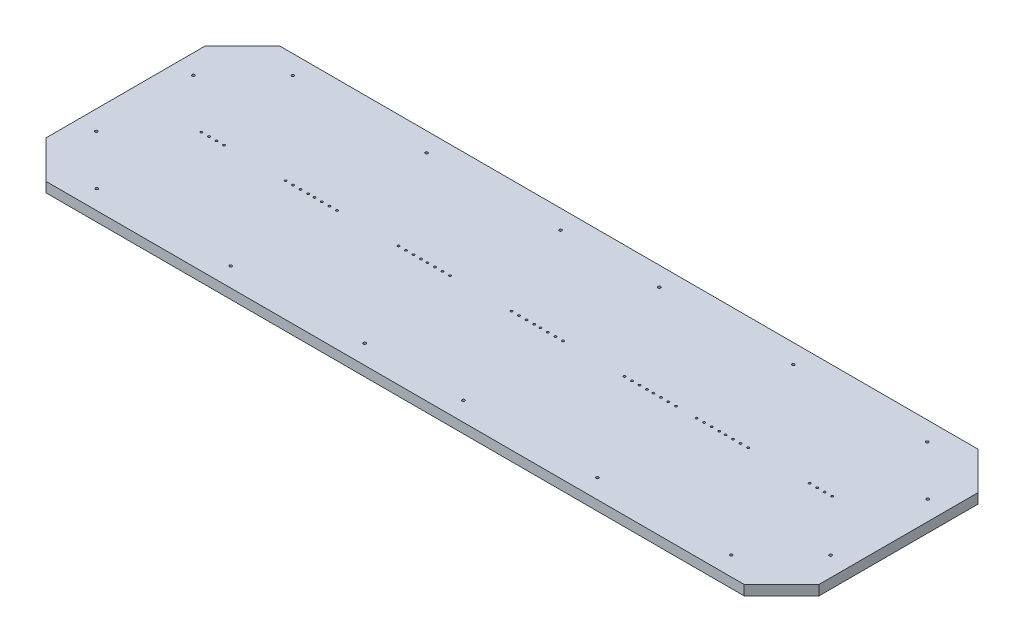
SolidWorks part; units mm, degrees
material "Pin"
ref_plane "Plan de face" through (0, 0, 0) normal (0, 0, 1) x (1, 0, 0)
ref_plane "Plan de dessus" through (0, 0, 0) normal (0, 1, 0) x (1, 0, 0)
ref_plane "Plan de droite" through (0, 0, 0) normal (1, 0, 0) x (0, 0, -1)
sketch "Esquisse1" plane through (0, 0, 0) normal (0, 1, 0) x (1, 0, 0)
  line L0 (-615.95, 126.475) -> (-615.95, -126.475)
  line L1 (-615.95, -126.475) -> (-555.95, -186.475)
  line L2 (-555.95, -186.475) -> (555.95, -186.475)
  line L3 (555.95, -186.475) -> (615.95, -126.475)
  line L4 (615.95, -126.475) -> (615.95, 126.475)
  line L5 (615.95, 126.475) -> (555.95, 186.475)
  line L6 (555.95, 186.475) -> (-555.95, 186.475)
  line L7 (-555.95, 186.475) -> (-615.95, 126.475)
  line L8 (0, 186.475) -> (0, -186.475) construction
  point P11 (0, 0)
  dimension "D1" = 135
  dimension "D3" = 1231.9
  dimension "D4" = 372.95
  dimension "D5" = 252.95
extrude "Boss.-Extru.1" add sketch "Esquisse1" along normal blind 15.875
hole_wizard "Fraisage pour vis à tête fraisée bombée #61" positions "Esquisse2" profile "Esquisse3" countersink size "#6" standard "Ansi Inch" end condition through all
sketch "Esquisse2" plane through (0, 0, 0) normal (0, -1, 0) x (-1, 0, 0)
  line L0 (0, 0) -> (0, -77.375) construction
  line L2 (0, 0) -> (138.1752, 0) construction
  point P0 (292.1, -156.075)
  point P6 (78.7, -156.075)
  point P8 (505.5, -156.075)
  point P12 (584.875, -77.375)
  point P28 (78.7, 156.075)
  point P29 (292.1, 156.075)
  point P30 (505.5, 156.075)
  point P31 (584.875, 77.375)
  point P32 (-78.7, 156.075)
  point P33 (-292.1, 156.075)
  point P34 (-505.5, 156.075)
  point P35 (-584.875, 77.375)
  point P36 (-584.875, -77.375)
  point P37 (-505.5, -156.075)
  point P38 (-292.1, -156.075)
  point P39 (-78.7, -156.075)
  dimension "D1" = 156.075
  dimension "D2" = 156.075
  dimension "D3" = 156.075
  dimension "D4" = 77.375
  dimension "D5" = 78.7
  dimension "D6" = 292.1
  dimension "D7" = 505.5
  dimension "D8" = 584.875
sketch "Esquisse3" plane through (-292.1, 0, 156.075) normal (1, 0, 0) x (0, 0, -1)
  line L0 (0, 0) -> (0, 15.875)
  line L1 (0, 15.875) -> (2.1526, 15.875)
  line L2 (2.1526, 15.875) -> (2.1526, 1.5998)
  line L3 (2.1526, 1.5998) -> (3.5433, 0)
  line L5 (3.5433, 0) -> (0, 0)
  line L6 (-2.1526, 1.5998) -> (-3.5433, 0) construction
  line L11 (0, -6.35) -> (0, 107.95) construction
  dimension "Diamètre du perçage jusqu'au prochain" = 4.3053
  dimension "Profondeur du perçage jusqu'au prochain" = 15.875
  dimension "Diamètre du fraisage entrant" = 7.0866
  dimension "Angle du fraisage entrant" = 82
hole_wizard "Chambrage pour vis à tête ronde bombée M31" positions "Esquisse4" profile "Esquisse5" counterbore size "M3" standard "Ansi Metric"
sketch "Esquisse4" plane through (0, 0, 0) normal (0, 1, 0) x (1, 0, 0)
  point P0 (-488, 5.1765)
  point P2 (-476, 5.1765)
  point P4 (-464, 5.1765)
  point P6 (-500, 5.1765)
  point P11 (-366, 5.1765)
  point P13 (-342, 5.1765)
  point P15 (-354, 5.1765)
  point P17 (-330, 5.1765)
  point P19 (-320, 5.1765)
  point P21 (-308, 5.1765)
  point P23 (-296, 5.1765)
  point P25 (-284, 5.1765)
  point P27 (-186, 5.1765)
  point P29 (-174, 5.1765)
  point P31 (-162, 5.1765)
  point P33 (-150, 5.1765)
  point P35 (-140, 5.1765)
  point P37 (-128, 5.1765)
  point P39 (-116, 5.1765)
  point P41 (-104, 5.1765)
  point P43 (-6, 5.1765)
  point P45 (6, 5.1765)
  point P47 (18, 5.1765)
  point P49 (30, 5.1765)
  point P51 (40, 5.1765)
  point P53 (52, 5.1765)
  point P55 (76, 5.1765)
  point P57 (64, 5.1765)
  point P59 (174, 5.1765)
  point P61 (186, 5.1765)
  point P63 (198, 5.1765)
  point P64 (210, 5.1765)
  point P66 (220, 5.1818)
  point P68 (232, 5.1818)
  point P70 (244, 5.1818)
  point P72 (256, 5.1818)
  point P74 (289, 5.1818)
  point P76 (301, 5.1818)
  point P78 (313, 5.1818)
  point P80 (325, 5.1818)
  point P82 (335, 5.1818)
  point P84 (347, 5.1818)
  point P86 (359, 5.1818)
  point P88 (371, 5.1818)
  point P90 (469, 5.1818)
  point P92 (481, 5.1818)
  point P94 (493, 5.1818)
  point P96 (505, 5.1818)
sketch "Esquisse5" plane through (-488, 0, -5.1765) normal (1, 0, 0) x (0, 0, -1)
  line L0 (0, 0) -> (0, 26)
  line L1 (0, 26) -> (1.7, 26)
  line L2 (1.7, 26) -> (1.7, 8)
  line L3 (1.7, 8) -> (3.5, 8)
  line L4 (3.5, 8) -> (3.5, 0)
  line L5 (3.5, 0) -> (0, 0)
  line L10 (0, 26) -> (-1.7, 26) construction
  line L11 (0, -6.35) -> (0, 107.95) construction
  dimension "Diamètre du perçage" = 3.4
  dimension "Profondeur du perçage" = 26
  dimension "Diamètre du chambrage" = 7
  dimension "Profondeur du chambrage" = 8
  dimension "Angle de pointe" = 180
